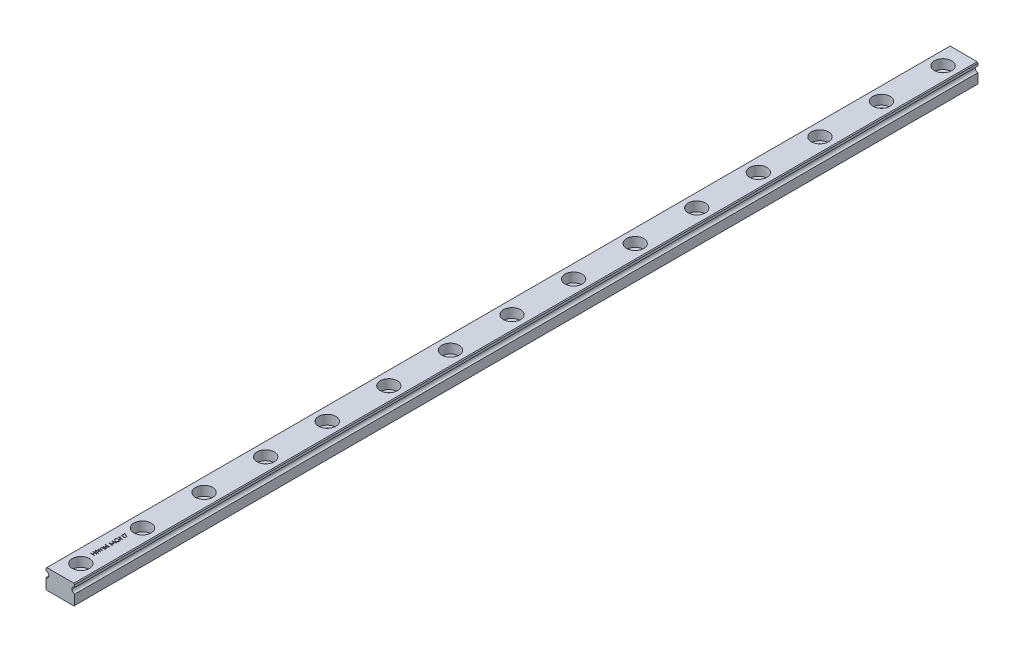
SolidWorks part; units mm, degrees
material "镀铬不锈钢"
ref_plane "前视基准面" through (0, 0, 0) normal (0, 0, 1) x (1, 0, 0)
ref_plane "上视基准面" through (0, 0, 0) normal (0, 1, 0) x (1, 0, 0)
ref_plane "右视基准面" through (0, 0, 0) normal (1, 0, 0) x (0, 0, -1)
sketch "草图1" plane through (0, 0, 0) normal (0, 0, 1) x (1, 0, 0)
  line L0 (0.2, 0) -> (0.8, 0)
  line L2 (-3.5, 4.6) -> (-3.5, 4)
  line L3 (0.8, 0) -> (3.3, 0)
  line L4 (-3.3, 0) -> (0.2, 0)
  line L5 (-3.5, 0.2) -> (-3.3, 0)
  line L6 (3.5, 0.2) -> (3.5, 2.6)
  line L7 (-3.3, 4.8) -> (-3.5, 4.6)
  line L8 (-3.5, 2.6) -> (-3.5, 0.2)
  line L9 (3.5, 4) -> (3.5, 4.6)
  line L10 (3.3, 0) -> (3.5, 0.2)
  line L11 (3.5, 4.6) -> (3.3, 4.8)
  line L12 (3.3, 4.8) -> (-3.3, 4.8)
  line L13 (0, 4.8) -> (0, 0) construction
  arc A0 (3.5, 4) -> (3.5, 2.6) centre (3.5, 3.3) ccw
  arc A1 (-3.5, 2.6) -> (-3.5, 4) centre (-3.5, 3.3) ccw
extrude "凸台-拉伸1" add sketch "草图1" against normal blind 220
hole_wizard "M2 六角凹头螺钉的柱形沉头孔1" positions "草图3" profile "草图2" counterbore size "M2" standard "ISO" end condition through all
sketch "草图3" plane through (1.648, 4.8, 19.9771) normal (0, 1, 0) x (-1, 0, 0)
  point P0 (1.648, -24.9771)
  dimension "D1" = 5
sketch "草图2" plane through (0, 4.8, -5) normal (1, 0, 0) x (0, 0, 1)
  line L0 (0, 0) -> (0, 4.8)
  line L1 (0, 4.8) -> (1.2, 4.8)
  line L3 (1.2, 4.8) -> (1.2, 2.3)
  line L4 (1.2, 2.3) -> (2.1, 2.3)
  line L5 (2.1, 2.3) -> (2.1, 0)
  line L7 (2.1, 0) -> (0, 0)
  line L11 (0, -6.35) -> (0, 107.95) construction
  dimension "通孔孔直径" = 2.4
  dimension "通孔孔深度" = 4.8
  dimension "柱形沉头孔直径" = 4.2
  dimension "柱形沉头孔深度" = 2.3
pattern_linear "阵列(线性)1" count 15 spacing 15 along (0, 0, -1) of "M2 六角凹头螺钉的柱形沉头孔1"
sketch "草图6" plane through (0, 4.8, 0) normal (0, 1, 0) x (1, 0, 0)
  line L0 (0, 5) -> (0, 20) construction
  text T0 "HIWIN MGN7" font "Century Gothic" height 1
extrude "切除-拉伸1" cut sketch "草图6" against normal blind 0.1
equation "\"D1@凸台-拉伸1\" = 2 * \"D1@草图3\" + \"D3@阵列(线性)1\" *  ( \"D1@阵列(线性)1\"  - 1) "
